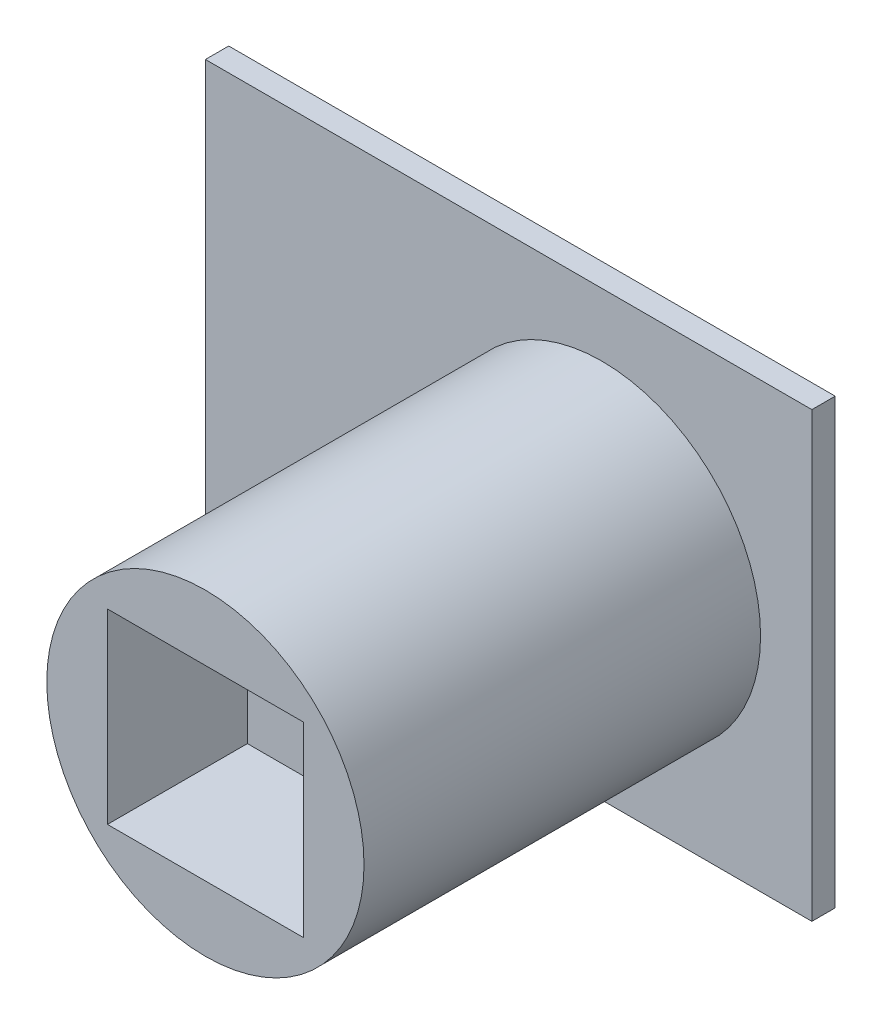
SolidWorks part; units mm, degrees
ref_plane "Alzado" through (0, 0, 0) normal (0, 0, 1) x (1, 0, 0)
ref_plane "Planta" through (0, 0, 0) normal (0, 1, 0) x (1, 0, 0)
ref_plane "Vista lateral" through (0, 0, 0) normal (1, 0, 0) x (0, 0, -1)
sketch "Croquis1" plane through (0, 0, 0) normal (0, 0, 1) x (1, 0, 0)
  line L1 (-65, -47.5) -> (65, -47.5)
  line L2 (-65, -47.5) -> (-65, 47.5)
  line L3 (-65, 47.5) -> (65, 47.5)
  line L4 (65, -47.5) -> (65, 47.5)
  line L5 (-65, -47.5) -> (65, 47.5) construction
  line L6 (-65, 47.5) -> (65, -47.5) construction
  point P0 (0, 0)
  dimension "D1" = 130
  dimension "D2" = 95
extrude "Saliente-Extruir1" add sketch "Croquis1" along normal blind 5
sketch "Croquis2" plane through (0, 0, 5) normal (0, 0, 1) x (1, 0, 0)
  line L0 (0, 0) -> (20, 0) construction
  circle A0 centre (20, 0) radius 34
  dimension "D2" = 68
  dimension "D1" = 20
extrude "Saliente-Extruir2" add sketch "Croquis2" along normal blind 85
sketch "Croquis3" plane through (0, 0, 90) normal (0, 0, 1) x (1, 0, 0)
  line L1 (-1, -20) -> (41, -20)
  line L2 (-1, -20) -> (-1, 20)
  line L3 (-1, 20) -> (41, 20)
  line L4 (41, -20) -> (41, 20)
  line L5 (-1, -20) -> (41, 20) construction
  line L6 (-1, 20) -> (41, -20) construction
  point P0 (20, 0)
  dimension "D1" = 42
  dimension "D2" = 40
extrude "Cortar-Extruir1" cut sketch "Croquis3" against normal blind 30
ref_plane "Plano1" through (0, 0, 0) normal (0, -1, 0) x (-1, 0, 0)
